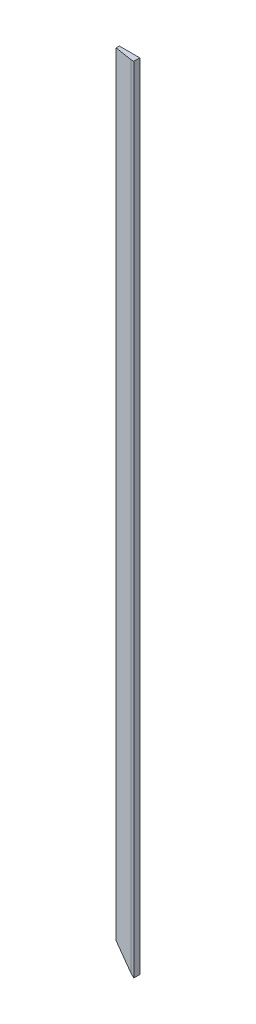
SolidWorks part; units mm, degrees
material "Pine"
ref_plane "Front Plane" through (0, 0, 0) normal (0, 0, 1) x (1, 0, 0)
ref_plane "Top Plane" through (0, 0, 0) normal (0, 1, 0) x (1, 0, 0)
ref_plane "Right Plane" through (0, 0, 0) normal (1, 0, 0) x (0, 0, -1)
sketch "Sketch1" plane through (0, 0, 0) normal (0, 1, 0) x (1, 0, 0)
  line L0 (0, 0) -> (53.975, 0)
  line L1 (53.975, 0) -> (53.975, -15.875)
  line L2 (53.975, -15.875) -> (46.355, -15.875)
  line L3 (46.355, -15.875) -> (0, -8.255)
  line L4 (0, -8.255) -> (0, 0)
  dimension "D1" = 53.975
  dimension "D2" = 15.875
  dimension "D3" = 8.255
  dimension "D4" = 7.62
extrude "Boss-Extrude1" add sketch "Sketch1" along normal blind 2092.325
sketch "Sketch2" plane through (0, 0, 15.875) normal (0, 0, 1) x (1, 0, 0)
  line L0 (53.975, 2092.325) -> (0, 2038.35)
  line L1 (0, 2092.325) -> (0, 0) construction
  line L2 (0, 2038.35) -> (0, 2092.325)
  line L3 (0, 2092.325) -> (53.975, 2092.325)
  dimension "D1" = 45
extrude "Cut-Extrude1" [suppressed] cut sketch "Sketch2" against normal through all
sketch "Sketch3" plane through (0, 0, 15.875) normal (0, 0, 1) x (1, 0, 0)
  line L0 (53.975, 0) -> (0, 53.975)
  line L1 (0, 2092.325) -> (0, 0) construction
  line L2 (0, 53.975) -> (0, 0)
  line L3 (0, 0) -> (53.975, 0)
  dimension "D1" = 45
extrude "Cut-Extrude2" cut sketch "Sketch3" against normal through all
